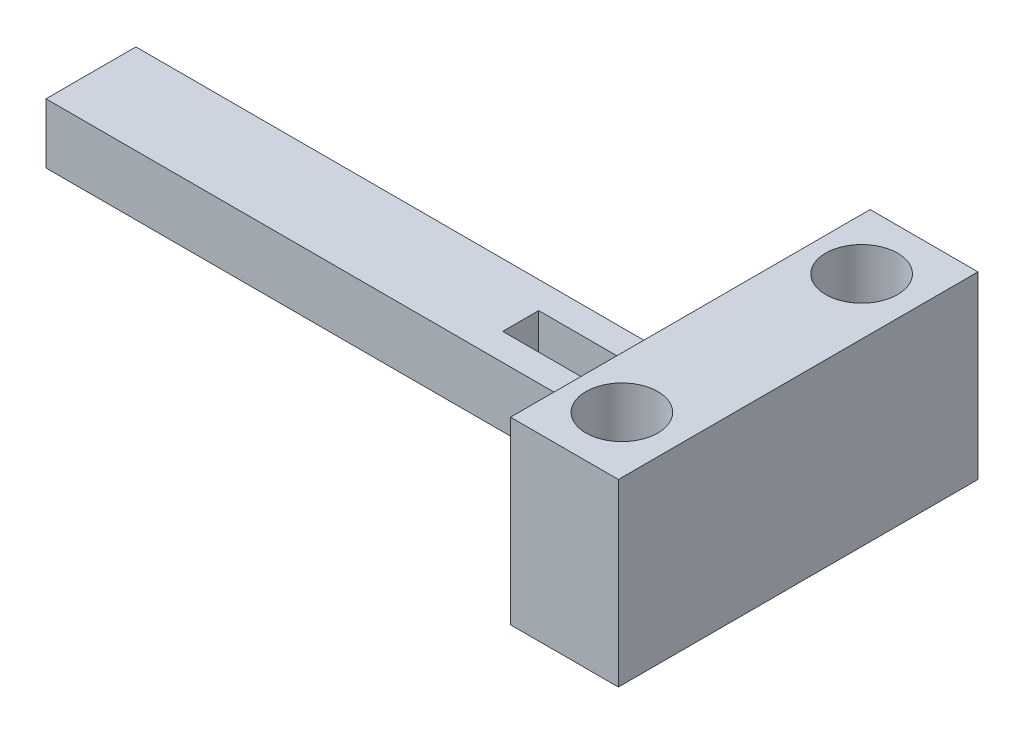
SolidWorks part; units mm, degrees
ref_plane "Front Plane" through (0, 0, 0) normal (0, 0, 1) x (1, 0, 0)
ref_plane "Top Plane" through (0, 0, 0) normal (0, 1, 0) x (1, 0, 0)
ref_plane "Right Plane" through (0, 0, 0) normal (1, 0, 0) x (0, 0, -1)
sketch "Sketch1" plane through (0, 0, 0) normal (0, 1, 0) x (1, 0, 0)
  line L0 (-55, 0) -> (55, 0) construction
  line L1 (12.7, -1.905) -> (-12.7, -1.905)
  line L2 (12.7, -1.905) -> (12.7, 1.905)
  line L3 (12.7, 1.905) -> (-12.7, 1.905)
  line L4 (-12.7, -1.905) -> (-12.7, 1.905)
  line L5 (12.7, -1.905) -> (-12.7, 1.905) construction
  line L6 (12.7, 1.905) -> (-12.7, -1.905) construction
  line L7 (5.5123, 0.762) -> (10.5923, 0.762)
  line L8 (5.5123, 0.762) -> (5.5123, -0.762)
  line L9 (5.5123, -0.762) -> (10.5923, -0.762)
  line L10 (10.5923, 0.762) -> (10.5923, -0.762)
  line L11 (5.5123, 0.762) -> (10.5923, -0.762) construction
  line L12 (5.5123, -0.762) -> (10.5923, 0.762) construction
  point P0 (0, 0)
  point P6 (8.0523, 0)
  dimension "D1" = 25.4
  dimension "D2" = 3.81
  dimension "D3" = 1.524
  dimension "D4" = 5.08
  dimension "D5" = 8.0523
extrude "Boss-Extrude1" add sketch "Sketch1" along normal blind 2.54
sketch "Sketch3" plane through (12.7, 0, 0) normal (1, 0, 0) x (0, 0, -1)
  line L0 (0, 2.794) -> (0, -2.794) construction
  line L1 (-7.62, 6.4129) -> (7.62, 6.4129)
  line L2 (-7.62, 6.4129) -> (-7.62, -1.2071)
  line L3 (-7.62, -1.2071) -> (7.62, -1.2071)
  line L4 (7.62, 6.4129) -> (7.62, -1.2071)
  line L5 (-7.62, 6.4129) -> (7.62, -1.2071) construction
  line L6 (-7.62, -1.2071) -> (7.62, 6.4129) construction
  line L7 (8.382, 0) -> (-8.382, 0) construction
  point P0 (0, 2.6029)
  dimension "D1" = 5.715
  dimension "D2" = 3.81
  dimension "D3" = 1.2071
extrude "Boss-Extrude2" add sketch "Sketch3" along normal blind 4.572
sketch "Sketch4" plane through (0, 6.4129, 0) normal (0, 1, 0) x (1, 0, 0)
  line L0 (12.7, 7.62) -> (12.7, -7.62) construction
  line L1 (-2.794, 0) -> (2.794, 0) construction
  circle A0 centre (14.8798, -5.08) radius 1.524
  circle A1 centre (14.8798, 5.08) radius 1.524
  dimension "D1" = 3.048
  dimension "D2" = 2.1798
  dimension "D3" = 5.08
extrude "Cut-Extrude1" cut sketch "Sketch4" against normal through all
